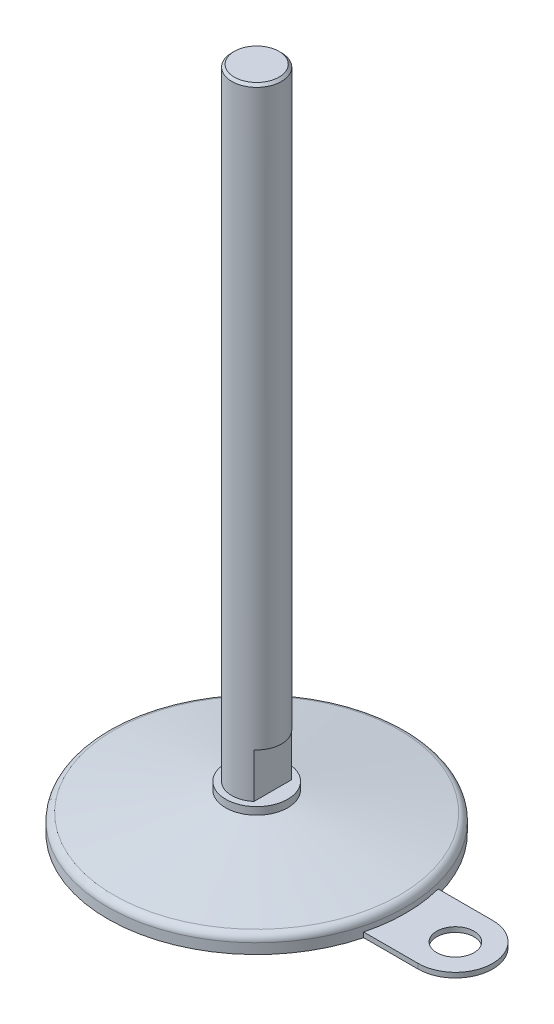
SolidWorks part; units mm, degrees
material "V2a"
ref_plane "Vorne" through (0, 0, 0) normal (0, 0, 1) x (1, 0, 0)
ref_plane "Oben" through (0, 0, 0) normal (0, 1, 0) x (1, 0, 0)
ref_plane "Rechts" through (0, 0, 0) normal (1, 0, 0) x (0, 0, -1)
sketch "Skizze1" plane through (0, 0, 0) normal (0, 0, 1) x (1, 0, 0)
  line L0 (0, 290) -> (0, -20) construction
  line L1 (0, 0) -> (-55, 0)
  line L2 (-60, 2) -> (-60, 6.1072)
  line L3 (-57.5209, 9.0616) -> (-12.5, 17)
  line L4 (-60, 2) -> (-55, 2)
  line L5 (-12.5, 17) -> (-31.5565, 17) construction
  line L6 (0, 270) -> (0, 0)
  line L7 (-10, 20) -> (-10, 270)
  line L8 (-10, 270) -> (0, 270)
  line L10 (-12.5, 17) -> (-12.5, 20)
  line L11 (-12.5, 20) -> (-10, 20)
  line L12 (-55, 2) -> (-55, 0)
  arc A0 (-60, 6.1072) -> (-57.5209, 9.0616) centre (-57, 6.1072) cw
  dimension "D1" = 3
  dimension "D2" = 110
  dimension "D3" = 120
  dimension "D4" = 3
  dimension "D5" = 20
  dimension "D6" = 25
  dimension "D7" = 20
  dimension "D8" = 10
  dimension "D9" = 2
  dimension "D10" = 20
  dimension "D11" = 20
  dimension "D12" = 250
revolve "Rotation1" add sketch "Skizze1" angle 360 about L0
cosmetic thread "Gewindedarstellung1" parameters "D2"=12.8
chamfer "Fase1" distance 1 angle 45 1 edges at (-10, 270, 0)
sketch "Skizze2" plane through (0, 0, 0) normal (0, 0, 1) x (1, 0, 0)
  line L1 (-10, 38) -> (-6.5, 38)
  line L2 (-10, 38) -> (-10, 20)
  line L3 (-10, 20) -> (-6.5, 20)
  line L4 (-6.5, 38) -> (-6.5, 20)
  line L5 (10, 38) -> (6.5, 38)
  line L6 (10, 38) -> (10, 20)
  line L7 (10, 20) -> (6.5, 20)
  line L8 (6.5, 38) -> (6.5, 20)
  line L12 (0, 35.9422) -> (0, 13.447) construction
  line L13 (-10, 269) -> (-10, 20) construction
  line L14 (10, 20) -> (10, 269) construction
  line L15 (12.5, 20) -> (-12.5, 20) construction
  dimension "D1" = 13
  dimension "D2" = 18
extrude "Schnitt-Linear austragen1" cut sketch "Skizze2" against normal mid plane 20
sketch "Skizze3" plane through (0, 2, 0) normal (0, -1, 0) x (1, 0, 0)
  line L0 (0, 0) -> (60, 0) construction
  line L1 (0, 15) -> (0, -15)
  line L2 (0, 15) -> (80, 15)
  line L3 (0, -15) -> (80, -15)
  line L4 (60, 0) -> (80, 0) construction
  circle A0 centre (0, 0) radius 60 construction
  arc A1 (80, -15) -> (80, 15) centre (80, 0) ccw
  circle A2 centre (80, 0) radius 7.5
  dimension "D1" = 35
  dimension "D2" = 30
  dimension "D3" = 30
  dimension "D4" = 15
extrude "Aufsatz-Linear austragen1" add sketch "Skizze3" against normal blind 2
